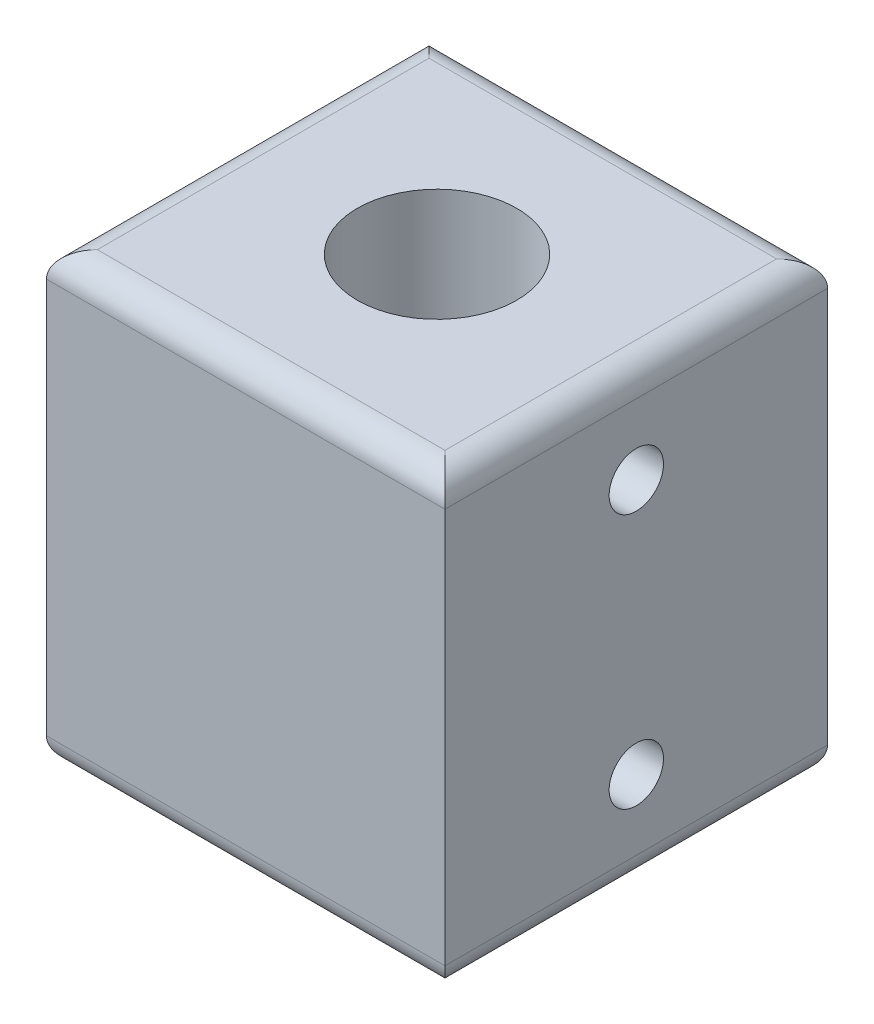
SolidWorks part; units mm, degrees
material "6061 Alloy"
ref_plane "Front Plane" through (0, 0, 0) normal (0, 0, 1) x (1, 0, 0)
ref_plane "Top Plane" through (0, 0, 0) normal (0, 1, 0) x (1, 0, 0)
ref_plane "Right Plane" through (0, 0, 0) normal (1, 0, 0) x (0, 0, -1)
sketch "Sketch1" plane through (0, 0, 0) normal (0, 0, 1) x (1, 0, 0)
  line L0 (0, 0) -> (19.845, 0)
  line L1 (0, 0) -> (0, 22.225)
  line L2 (0, 22.225) -> (19.845, 22.225)
  line L3 (19.845, 22.225) -> (19.845, 0)
  dimension "D1" = 22.225
  dimension "D2" = 19.845
extrude "Body" add sketch "Sketch1" along normal blind 19.05
sketch "Sketch2" plane through (0, 22.225, 0) normal (0, 1, 0) x (1, 0, 0)
  line L0 (9.9225, 0) -> (9.9225, -19.05) construction
  line L1 (19.845, 0) -> (0, 0) construction
  line L2 (19.845, -19.05) -> (0, -19.05) construction
  line L3 (0, -9.525) -> (19.845, -9.525) construction
  line L4 (0, -19.05) -> (0, 0) construction
  line L5 (19.845, -19.05) -> (19.845, 0) construction
  circle A0 centre (9.9225, -9.525) radius 3.9688
  dimension "D1" = 7.9375
extrude "Yaw Axle Opening" cut sketch "Sketch2" against normal through all contours L0 A0 L3 | L3 A0 L0 | L0 A0 L3 | L3 A0 L0
hole_wizard "#6-32 Tapped Hole1" positions "3DSketch1" profile "Sketch3" tap size "#6-32" standard "Ansi Inch"
sketch3d "3DSketch1"
  line L0 (0, 0, 9.525) -> (0, 22.225, 9.525) construction
  line L1 (0, 0, 19.05) -> (0, 0, 0) construction
  line L3 (0, 17.4625, 0) -> (0, 17.4625, 19.05) construction
  line L4 (0, 4.7625, 0) -> (0, 4.7625, 19.05) construction
  line L5 (0, 22.225, 19.05) -> (0, 22.225, 0) construction
  line L6 (0, 22.225, 19.05) -> (0, 0, 19.05) construction
  line L7 (0, 22.225, 0) -> (0, 0, 0) construction
  point P0 (0, 17.4625, 9.525)
  point P2 (0, 4.7625, 9.525)
  dimension "D1" = 12.7
  dimension "D2" = 4.7625
sketch "Sketch3" plane through (0, 17.4625, 9.525) normal (0, 1, 0) x (0, 0, 1)
  line L0 (0, 0) -> (0, 5.5752)
  line L1 (0, 5.5752) -> (1.3525, 4.7625)
  line L2 (1.3525, 4.7625) -> (1.3525, 0)
  line L5 (1.3525, 0) -> (0, 0)
  line L10 (0, 5.5752) -> (-1.3526, 4.7625) construction
  line L11 (0, -6.35) -> (0, 107.95) construction
  dimension "Tap Drill Dia." = 2.7051
  dimension "Tap Drill Depth" = 4.7625
  dimension "Drill Angle" = 118
cosmetic thread "Hole Thread1" parameters "D1"=4.7625, "D2"=3.5052
cosmetic thread "Hole Thread2" parameters "D1"=4.7625, "D2"=3.5052
hole_wizard "#6-32 Tapped Hole2" positions "3DSketch2" profile "Sketch4" tap size "#6-32" standard "Ansi Inch"
sketch3d "3DSketch2"
  line L6 (19.845, 0, 9.525) -> (19.845, 22.225, 9.525) construction
  line L7 (19.845, 0, 19.05) -> (19.845, 0, 0) construction
  line L17 (19.845, 17.4625, 19.05) -> (19.845, 17.4625, 0) construction
  line L18 (19.845, 0, 19.05) -> (19.845, 22.225, 19.05) construction
  line L19 (19.845, 0, 0) -> (19.845, 22.225, 0) construction
  line L20 (19.845, 4.7625, 19.05) -> (19.845, 4.7625, 0) construction
  line L21 (19.845, 22.225, 19.05) -> (19.845, 22.225, 0) construction
  point P0 (19.845, 17.4625, 9.525)
  point P2 (19.845, 4.7625, 9.525)
  dimension "D1" = 4.7625
  dimension "D2" = 12.7
sketch "Sketch4" plane through (19.845, 17.4625, 9.525) normal (0, 1, 0) x (0, 0, -1)
  line L0 (0, 0) -> (0, 5.5752)
  line L1 (0, 5.5752) -> (1.3525, 4.7625)
  line L2 (1.3525, 4.7625) -> (1.3525, 0)
  line L5 (1.3525, 0) -> (0, 0)
  line L10 (0, 5.5752) -> (-1.3526, 4.7625) construction
  line L11 (0, -6.35) -> (0, 107.95) construction
  dimension "Tap Drill Dia." = 2.7051
  dimension "Tap Drill Depth" = 4.7625
  dimension "Drill Angle" = 118
cosmetic thread "Hole Thread3" parameters "D1"=4.7625, "D2"=3.5052
cosmetic thread "Hole Thread4" parameters "D1"=4.7625, "D2"=3.5052
hole_wizard "#6-32 Tapped Hole3" positions "Sketch6" profile "Sketch5" tap size "#6-32" standard "Ansi Inch"
sketch "Sketch6" plane through (0, 0, 0) normal (0, 0, -1) x (-1, 0, 0)
  line L0 (-9.9225, 22.225) -> (-9.9225, 17.225) construction
  line L1 (-19.845, 22.225) -> (0, 22.225) construction
  point P0 (-9.9225, 17.225)
  dimension "D1" = 5
sketch "Sketch5" plane through (9.9225, 17.225, 0) normal (1, 0, 0) x (0, 1, 0)
  line L0 (0, 0) -> (0, 4.6227)
  line L1 (0, 4.6227) -> (1.3525, 3.81)
  line L2 (1.3525, 3.81) -> (1.3525, 0)
  line L5 (1.3525, 0) -> (0, 0)
  line L10 (0, 4.6227) -> (-1.3526, 3.81) construction
  line L11 (0, -6.35) -> (0, 107.95) construction
  dimension "Tap Drill Dia." = 2.7051
  dimension "Tap Drill Depth" = 3.81
  dimension "Drill Angle" = 118
cosmetic thread "Hole Thread5" parameters "D1"=3.81, "D2"=3.5052
fillet "Fillet1" radius 1.27 8 edges at (9.9225, 22.225, 0) (0, 22.225, 9.525) (19.845, 22.225, 9.525) (9.9225, 22.225, 19.05) (9.9225, 0, 0) (19.845, 0, 9.525) (9.9225, 0, 19.05) (0, 0, 9.525)
